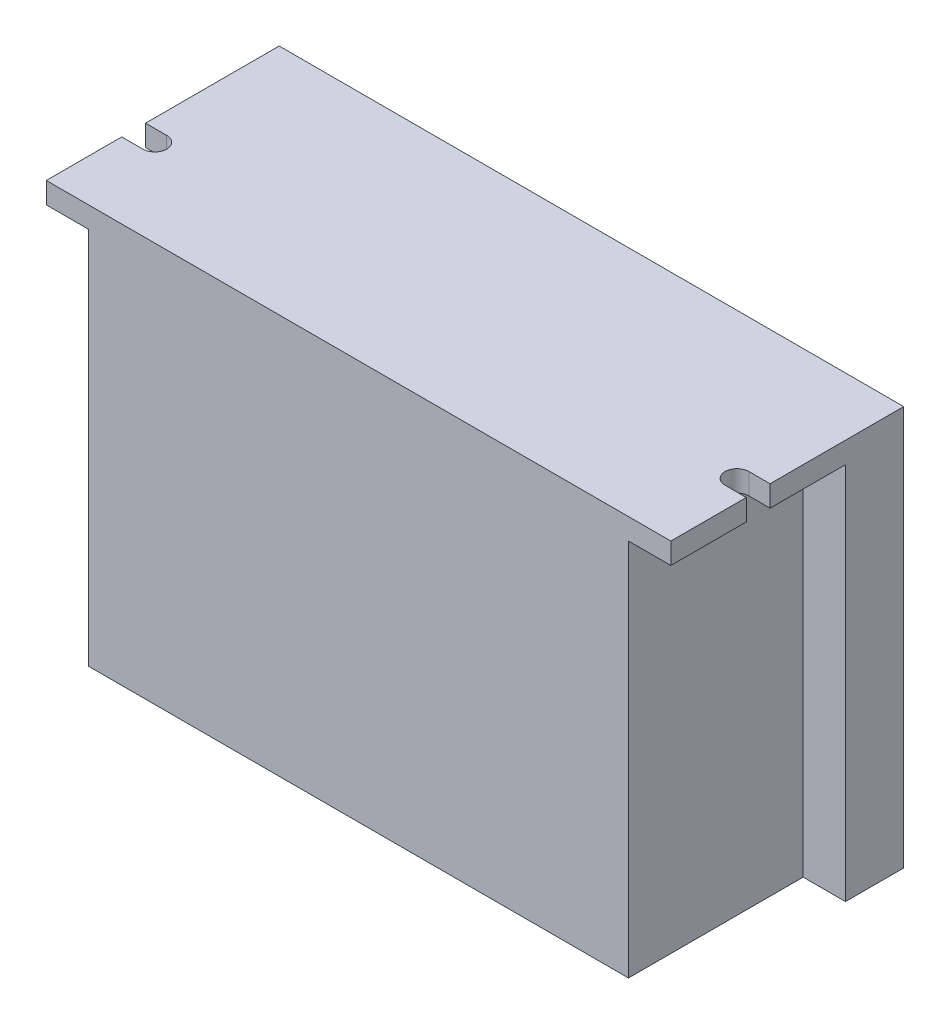
SolidWorks part; units mm, degrees
ref_plane "Plan de face" through (0, 0, 0) normal (0, 0, 1) x (1, 0, 0)
ref_plane "Plan de dessus" through (0, 0, 0) normal (0, 1, 0) x (1, 0, 0)
ref_plane "Plan de droite" through (0, 0, 0) normal (1, 0, 0) x (0, 0, -1)
sketch "Esquisse1" plane through (0, 0, 0) normal (0, 0, 1) x (1, 0, 0)
  line L1 (-64.5968, 31.3656) -> (53.4032, 31.3656)
  line L2 (-64.5968, 31.3656) -> (-64.5968, -44.1344)
  line L3 (-64.5968, -44.1344) -> (53.4032, -44.1344)
  line L4 (53.4032, 31.3656) -> (53.4032, -44.1344)
  dimension "D1" = 118
  dimension "D2" = 75.5
extrude "Boss.-Extru.1" add sketch "Esquisse1" along normal blind 11
sketch "Esquisse2" plane through (0, 0, 11) normal (0, 0, 1) x (1, 0, 0)
  line L0 (-64.5968, 31.3656) -> (53.4032, 31.3656)
  line L1 (53.4032, 31.3656) -> (53.4032, 27.3656)
  line L2 (53.4032, -44.1344) -> (53.4032, 31.3656) construction
  line L3 (53.4032, 27.3656) -> (45.4032, 27.3656)
  line L4 (45.4032, 27.3656) -> (45.4032, -44.1344)
  line L5 (-64.5968, -44.1344) -> (53.4032, -44.1344) construction
  line L6 (45.4032, -44.1344) -> (-56.5968, -44.1344)
  line L7 (-56.5968, -44.1344) -> (-56.5968, 27.3656)
  line L8 (-56.5968, 27.3656) -> (-64.5968, 27.3656)
  line L9 (-64.5968, 31.3656) -> (-64.5968, -44.1344) construction
  line L10 (-64.5968, 27.3656) -> (-64.5968, 31.3656)
  dimension "D1" = 8
  dimension "D2" = 8
  dimension "D3" = 4
extrude "Boss.-Extru.2" add sketch "Esquisse2" along normal blind 33
sketch "Esquisse3" plane through (0, 27.3656, 0) normal (0, -1, 0) x (1, 0, 0)
  line L0 (-64.5968, 29.75) -> (-60.5968, 29.75)
  line L1 (-64.5968, 44) -> (-64.5968, 11) construction
  line L2 (-64.5968, 25.25) -> (-60.5968, 25.25)
  line L4 (-64.5968, 29.75) -> (-64.5968, 25.25)
  line L5 (53.4032, 29.75) -> (49.4032, 29.75)
  line L6 (53.4032, 44) -> (53.4032, 11) construction
  line L7 (53.4032, 29.75) -> (53.4032, 25.25)
  line L8 (53.4032, 25.25) -> (49.4032, 25.25)
  arc A0 (-60.5968, 25.25) -> (-60.5968, 29.75) centre (-60.5968, 27.5) ccw
  arc A1 (49.4032, 25.25) -> (49.4032, 29.75) centre (49.4032, 27.5) cw
  point P7 (-64.5968, 27.5)
  point P8 (-64.5968, 27.5)
  point P16 (53.4032, 27.5)
  point P17 (53.4032, 27.5)
  dimension "D1" = 4.5
  dimension "D2" = 4
extrude "Enlèv. mat.-Extru.1" cut sketch "Esquisse3" against normal up to next
